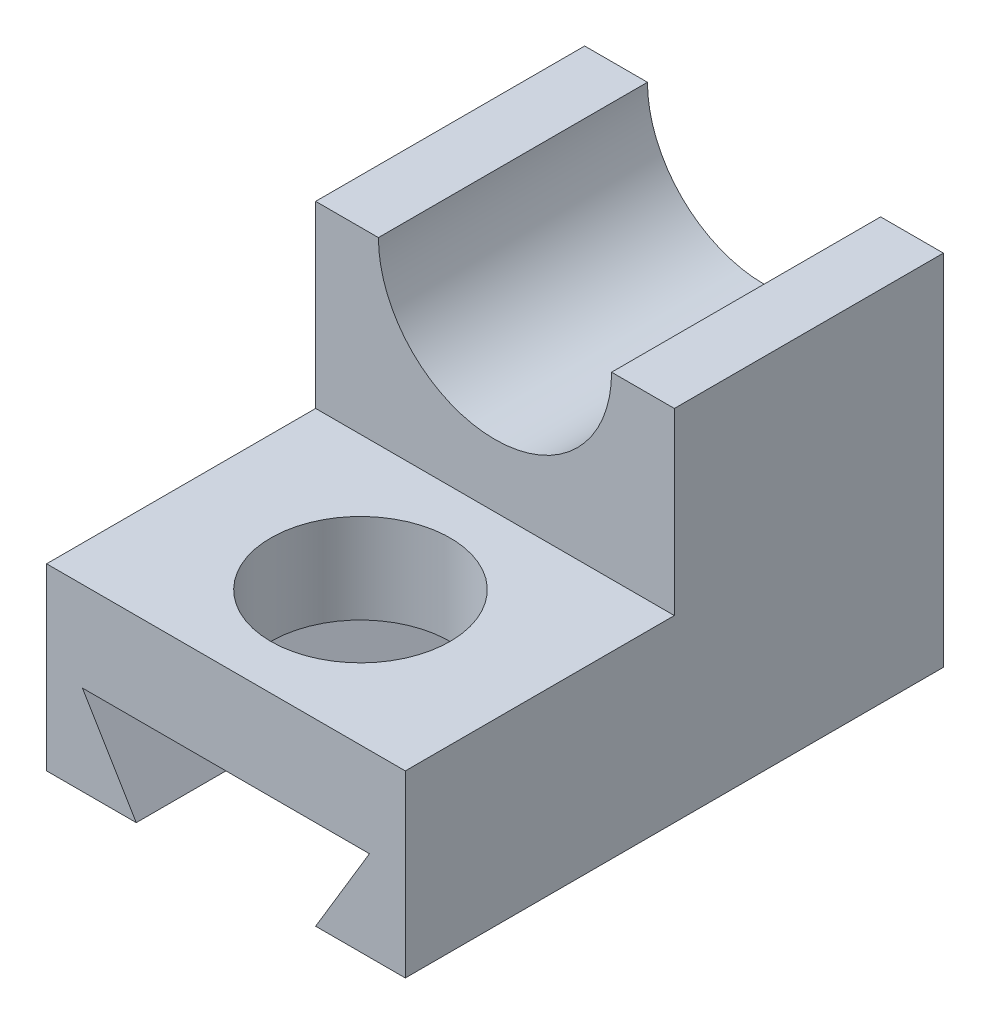
SolidWorks part; units mm, degrees
ref_plane "前视基准面" through (0, 0, 0) normal (0, 0, 1) x (1, 0, 0)
ref_plane "上视基准面" through (0, 0, 0) normal (0, 1, 0) x (1, 0, 0)
ref_plane "右视基准面" through (0, 0, 0) normal (1, 0, 0) x (0, 0, -1)
other "Configuration Table"
sketch "草图1" plane through (0, 0, 0) normal (1, 0, 0) x (0, 0, -1)
  line L2 (0, 0) -> (0, 20)
  line L3 (0, 20) -> (30, 20)
  line L5 (0, 0) -> (60, 0)
  line L6 (30, 20) -> (30, 40)
  line L7 (30, 40) -> (60, 40)
  line L8 (60, 0) -> (60, 40)
  point P8 (30, 0)
  point P9 (0, 0)
  point P10 (28.8883, 0)
  point P11 (0, 0)
  point P12 (24.9472, 0)
  point P13 (0, 0)
  point P14 (0, -0.3462)
  dimension "D1" = 40
  dimension "D2" = 30
  dimension "D3" = 60
  dimension "D4" = 20
extrude "凸台-拉伸1" add sketch "草图1" along normal mid plane 40
sketch "草图2" plane through (0, 0, 0) normal (0, 0, 1) x (1, 0, 0)
  line L0 (10, 0) -> (16, 10)
  line L1 (20, 0) -> (-20, 0) construction
  line L2 (16, 10) -> (-16, 10)
  line L3 (0, 0) -> (0, 11.6168) construction
  line L4 (-10, 0) -> (-16, 10)
  line L5 (-10, 0) -> (10, 0)
  point P9 (0, 10)
  dimension "D1" = 20
  dimension "D2" = 32
  dimension "D3" = 10
extrude "切除-拉伸2" cut sketch "草图2" against normal through all
sketch "草图3" plane through (0, 20, 0) normal (0, 1, 0) x (1, 0, 0)
  line L1 (20, 0) -> (-20, 0) construction
  circle A0 centre (0, 15) radius 10
  point P4 (0, 15)
  dimension "D2" = 20
  dimension "D1" = 15
extrude "切除-拉伸3" cut sketch "草图3" against normal through all
sketch "草图4" plane through (0, 0, -30) normal (0, 0, 1) x (1, 0, 0)
  line L0 (20, 40) -> (-20, 40) construction
  line L1 (-13, 40) -> (13, 40)
  arc A0 (-13, 40) -> (13, 40) centre (0, 40) ccw
  dimension "D1" = 13
extrude "切除-拉伸4" cut sketch "草图4" against normal through all
